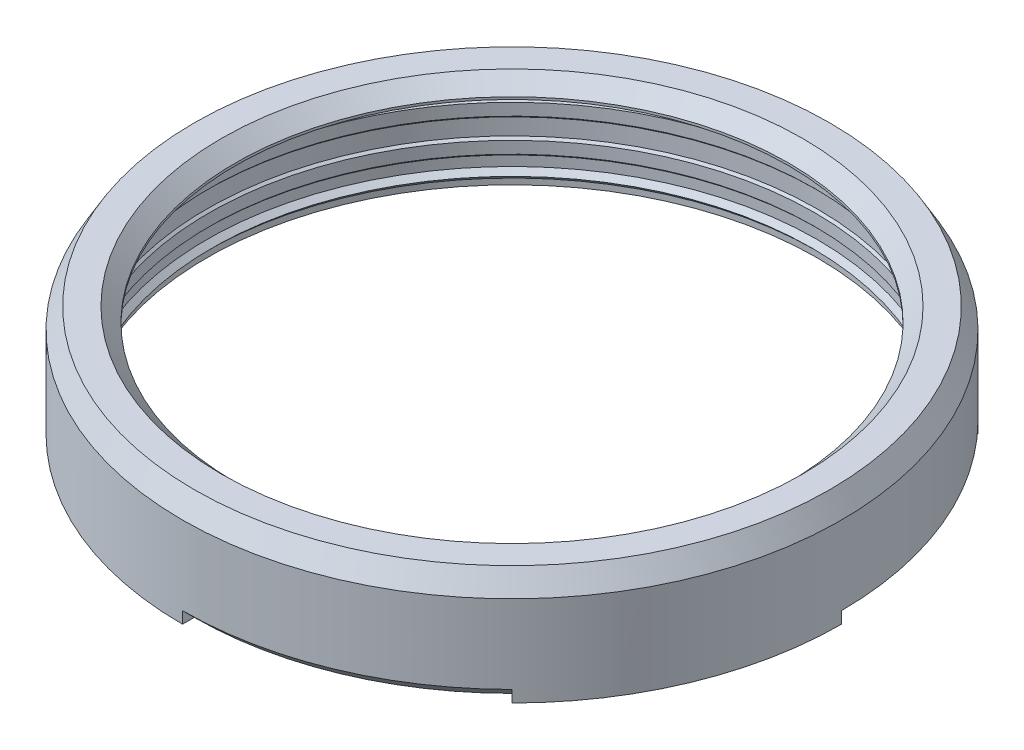
SolidWorks part; units mm, degrees
ref_plane "前视基准面" through (0, 0, 0) normal (0, 0, 1) x (1, 0, 0)
ref_plane "上视基准面" through (0, 0, 0) normal (0, 1, 0) x (1, 0, 0)
ref_plane "右视基准面" through (0, 0, 0) normal (1, 0, 0) x (0, 0, -1)
sketch "草图1" plane through (0, 0, 0) normal (0, 1, 0) x (1, 0, 0)
  circle A0 centre (0, 0) radius 28
  dimension "D1" = 56
extrude "凸台-拉伸1" add sketch "草图1" along normal blind 2
sketch "草图2" plane through (0, 0, 0) normal (0.2419, 0, -0.9703) x (-0.9703, 0, -0.2419)
  line L0 (25.93, -8) -> (25.93, -7.5)
  line L1 (25.93, -7.5) -> (25.505, -7.075)
  line L2 (25.505, -7.075) -> (25.93, -6.65)
  line L3 (25.93, -6.65) -> (25.93, -5.8)
  line L4 (25.93, -5.8) -> (25.74, -5.61)
  line L5 (25.74, -5.61) -> (25.74, -4.59)
  line L6 (25.74, -4.59) -> (25.93, -4.4)
  line L7 (25.93, -4.4) -> (25.93, -3)
  line L8 (25.93, -3) -> (25.74, -2.81)
  line L9 (25.74, -2.81) -> (25.74, -1.79)
  line L10 (25.74, -1.79) -> (25.93, -1.6)
  line L11 (25.93, -1.6) -> (25.93, -1.4)
  line L12 (24.53, 0) -> (28, 0)
  line L13 (28, 0) -> (28, -8)
  line L14 (28, -8) -> (25.93, -8)
  line L15 (25.8, -8) -> (27, -8) construction
  line L16 (25.8, -8) -> (25.8, -7.5) construction
  line L17 (0, 0) -> (0, 2.4316) construction
  arc A0 (25.93, -1.4) -> (24.53, 0) centre (24.53, -1.4) ccw
  dimension "D9" = 1.4
  dimension "D1" = 2.26
  dimension "D2" = 8
  dimension "D3" = 0.5
  dimension "D4" = 0.85
  dimension "D5" = 1.4
  dimension "D6" = 1.02
  dimension "D7" = 1.02
  dimension "D8" = 0.2
  dimension "D10" = 135
  dimension "D11" = 0.13
revolve "旋转1" add sketch "草图2" angle 360 about L17
sketch "草图4" plane through (0, 2, 0) normal (0, 1, 0) x (1, 0, 0)
  circle A0 centre (0, 0) radius 23.5
  circle A1 centre (0, 0) radius 28 construction
  dimension "D1" = 4.5
extrude "切除-拉伸1" cut sketch "草图4" against normal through all
sketch "草图5" plane through (0, 2, 0) normal (0, 1, 0) x (1, 0, 0)
  circle A1 centre (0, 0) radius 28
  circle A2 centre (0, 0) radius 28
  dimension "D1" = 0
extrude "切除-拉伸2" cut sketch "草图5" against normal blind 0.6
chamfer "倒角1" distance 1.2 angle 45 1 edges at (0, 1.4, 23.5)
chamfer "倒角2" distance 1.732 angle 30 1 edges at (0, 1.4, 28)
sketch "草图7" plane through (0, 0, 0) normal (0, 0, 1) x (1, 0, 0)
  line L0 (28, -8) -> (28, -7)
  line L1 (25.7027, -8) -> (49.7444, -8) construction
  line L2 (28, -7) -> (27, -8)
  line L3 (-28, -8) -> (28, -8) construction
  line L4 (27, -8) -> (28, -8)
  line L5 (28, -8) -> (28, -0.332) construction
  line L6 (0, 0) -> (0, 4.7309) construction
  dimension "D1" = 1
  dimension "D2" = 1
revolve "切除-旋转1" cut sketch "草图7" angle 45 about L6
pattern_circular "阵列(圆周)1" count 4 over 360 about axis through (0, 0, 0) along (0, 1, 0) of "切除-旋转1"
sketch "草图8" plane through (0, 0, 0) normal (0, -1, 0) x (1, 0, 0)
  circle A0 centre (0, 0) radius 24.32
  circle A1 centre (0, 0) radius 24.78
  circle A2 centre (0, 0) radius 23.5 construction
  dimension "D1" = 0.82
  dimension "D2" = 0.46
extrude "凸台-拉伸2" add sketch "草图8" along normal blind 0.5
